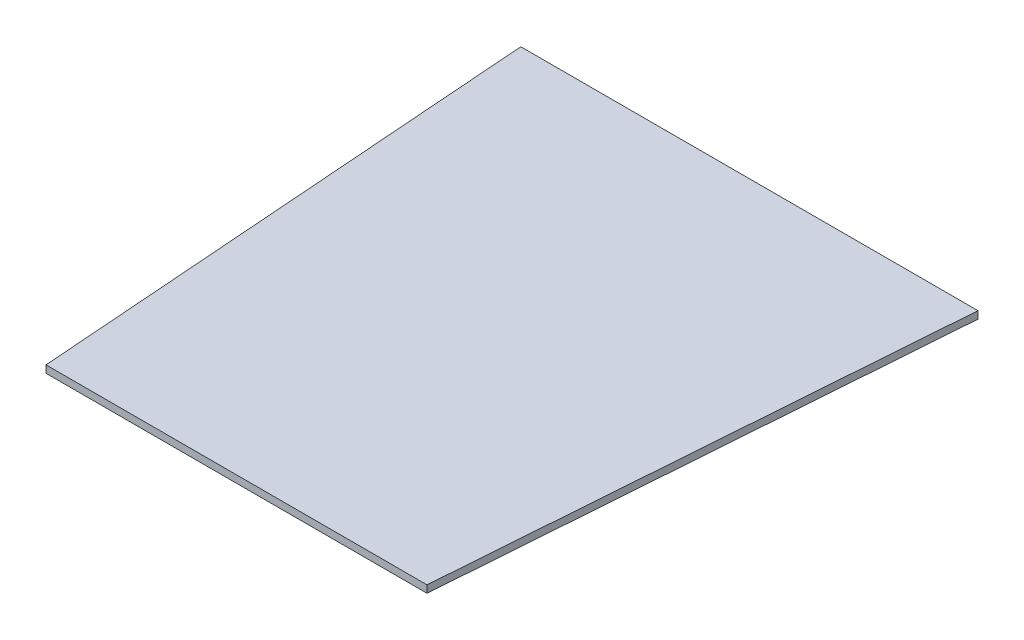
SolidWorks part; units mm, degrees
ref_plane "Front Plane" through (0, 0, 0) normal (0, 0, 1) x (1, 0, 0)
ref_plane "Top Plane" through (0, 0, 0) normal (0, 1, 0) x (1, 0, 0)
ref_plane "Right Plane" through (0, 0, 0) normal (1, 0, 0) x (0, 0, -1)
sketch "Sketch1" plane through (0, 0, 0) normal (0, 1, 0) x (1, 0, 0)
  line L1 (-156, -175) -> (156, -175)
  line L2 (-156, -175) -> (-156, 175)
  line L3 (-156, 175) -> (156, 175)
  line L4 (156, -175) -> (156, 175)
  line L5 (-156, -175) -> (156, 175) construction
  line L6 (-156, 175) -> (156, -175) construction
  point P0 (0, 0)
  dimension "D1" = 312
  dimension "D2" = 350
extrude "Boss-Extrude1" add sketch "Sketch1" along normal blind 5
sketch "Sketch3" plane through (0, 5, 0) normal (0, 1, 0) x (1, 0, 0)
  line L0 (156, 175) -> (130, -175)
  line L1 (-156, -175) -> (156, -175) construction
  line L2 (130, -175) -> (-130, -175)
  line L3 (-130, -175) -> (-156, 175)
  line L4 (-156, 175) -> (156, 175)
  point P9 (0, -175)
  line M5 (156, -175) -> (156, 175)
  line M7 (-156, 175) -> (-156, -175)
  line M8 (-156, -175) -> (156, -175)
  dimension "D1" = 260
extrude "Cut-Extrude1" cut sketch "Sketch3" against normal through all contours L0 M5 M8 | L3 M8 M7
